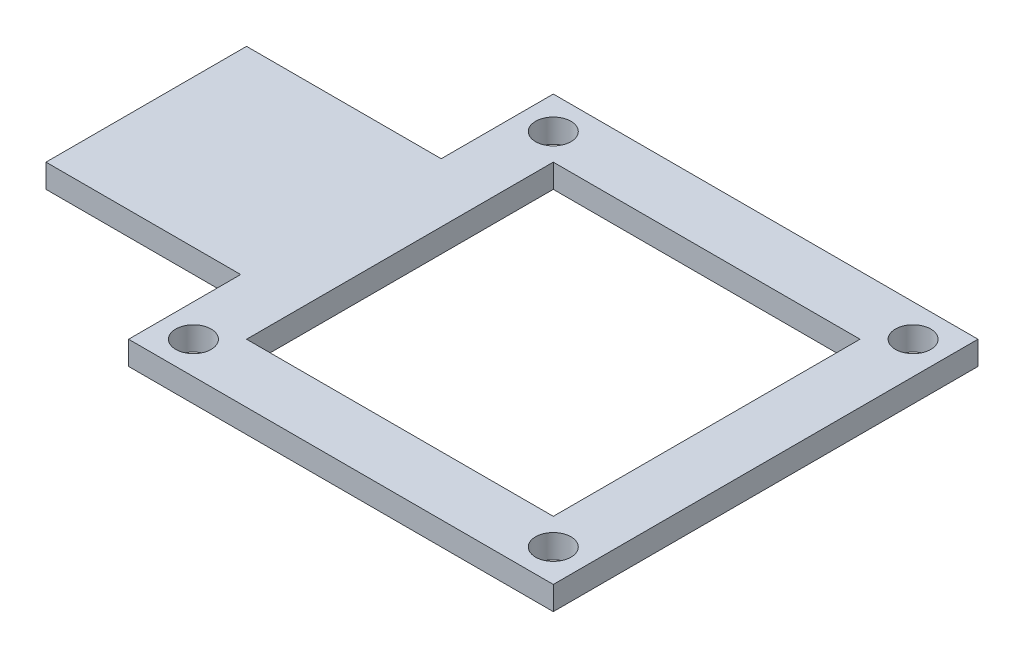
SolidWorks part; units mm, degrees
ref_plane "Alzado" through (0, 0, 0) normal (0, 0, 1) x (1, 0, 0)
ref_plane "Planta" through (0, 0, 0) normal (0, 1, 0) x (1, 0, 0)
ref_plane "Vista lateral" through (0, 0, 0) normal (1, 0, 0) x (0, 0, -1)
sketch "Croquis1" plane through (0, 0, 0) normal (0, 1, 0) x (1, 0, 0)
  line L0 (-13, -13) -> (-13, 13)
  line L1 (-18, -18) -> (18, -18)
  line L2 (-18, -18) -> (-18, 18)
  line L3 (-18, 18) -> (18, 18)
  line L4 (18, -18) -> (18, 18)
  line L5 (-18, -18) -> (18, 18) construction
  line L6 (-18, 18) -> (18, -18) construction
  line L7 (-1.5, -8.5) -> (-34.5, -8.5)
  line L8 (-1.5, -8.5) -> (-1.5, 8.5)
  line L9 (-1.5, 8.5) -> (-34.5, 8.5)
  line L10 (-34.5, -8.5) -> (-34.5, 8.5)
  line L11 (-1.5, -8.5) -> (-34.5, 8.5) construction
  line L12 (-1.5, 8.5) -> (-34.5, -8.5) construction
  line L13 (-13, 13) -> (13, 13)
  line L14 (13, -13) -> (13, 13)
  line L15 (-13, -13) -> (13, -13)
  line L16 (0, 0) -> (26.5357, 0) construction
  line L17 (0, 0) -> (0, 23.2513) construction
  circle A0 centre (-15.25, 15.25) radius 1.5
  circle A1 centre (-15.25, -15.25) radius 1.5
  circle A2 centre (15.25, -15.25) radius 1.5
  circle A3 centre (15.25, 15.25) radius 1.5
  point P0 (0, 0)
  point P6 (-18, 0)
  dimension "D5" = 3
  dimension "D1" = 36
  dimension "D2" = 52.5
  dimension "D3" = 17
  dimension "D6" = 15.25
  dimension "D4" = 5
extrude "Saliente-Extruir1" add sketch "Croquis1" along normal blind 2 contours L10 L7 L2 L9 | L15 L0 L7 L2 L1 L4 L3 L9 L13 L14 A1 A0 A2 A3 | L0 L9 L2 L7
